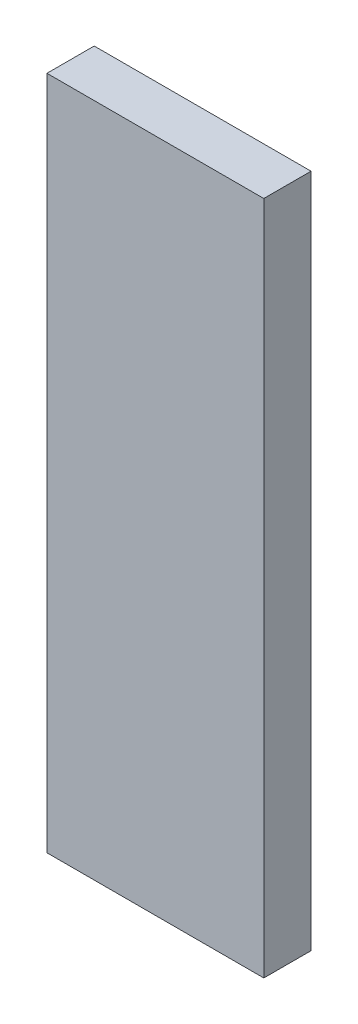
SolidWorks part; units mm, degrees
ref_plane "Front Plane" through (0, 0, 0) normal (0, 0, 1) x (1, 0, 0)
ref_plane "Top Plane" through (0, 0, 0) normal (0, 1, 0) x (1, 0, 0)
ref_plane "Right Plane" through (0, 0, 0) normal (1, 0, 0) x (0, 0, -1)
sketch "Sketch1" plane through (0, 0, 0) normal (0, 0, 1) x (1, 0, 0)
  line L0 (-5.6582, 31.0897) -> (-5.6582, -68.9103) construction
  line L1 (-21.7182, 31.0897) -> (10.4018, 31.0897)
  line L2 (-21.7182, 31.0897) -> (-21.7182, -68.9103)
  line L3 (-21.7182, -68.9103) -> (10.4018, -68.9103)
  line L4 (10.4018, 31.0897) -> (10.4018, -68.9103)
  dimension "D1" = 32.12
  dimension "D2" = 100
extrude "Boss-Extrude1" add sketch "Sketch1" along normal blind 7
